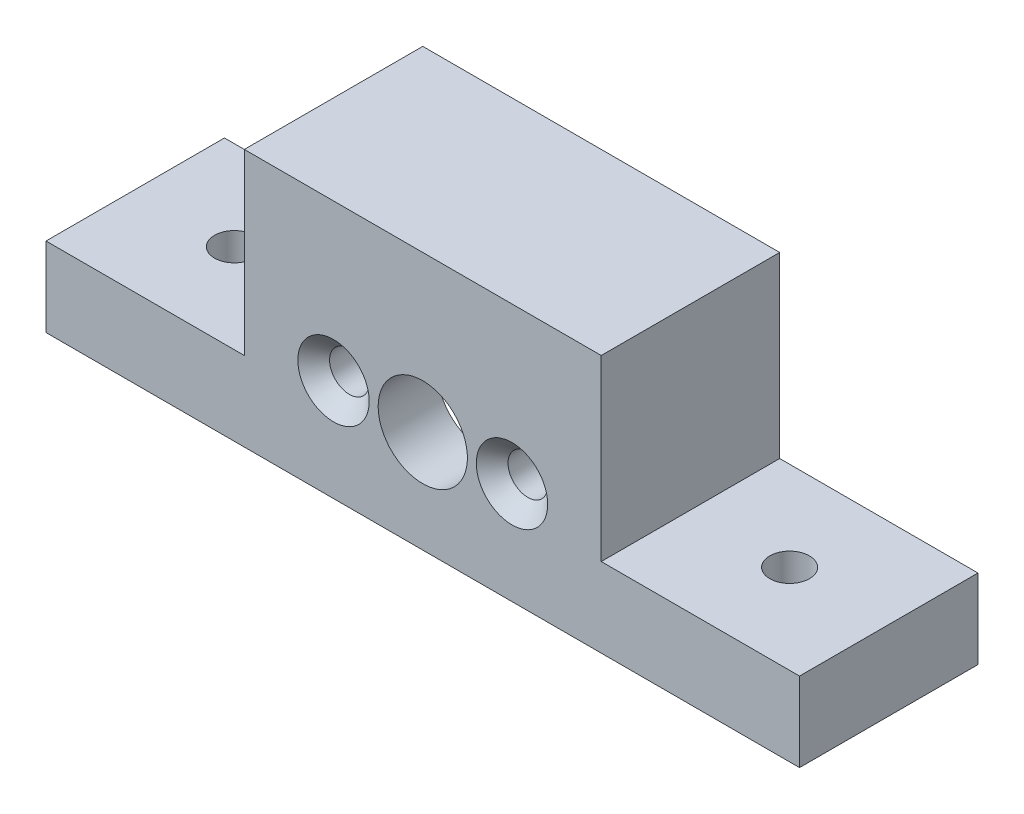
SolidWorks part; units mm, degrees
ref_plane "Front Plane" through (0, 0, 0) normal (0, 0, 1) x (1, 0, 0)
ref_plane "Top Plane" through (0, 0, 0) normal (0, 1, 0) x (1, 0, 0)
ref_plane "Right Plane" through (0, 0, 0) normal (1, 0, 0) x (0, 0, -1)
sketch "Sketch3" plane through (0, 0, 0) normal (0, 0, 1) x (1, 0, 0)
  line L1 (9, -6.5) -> (-9, -6.5)
  line L2 (9, -6.5) -> (9, 6.5)
  line L3 (9, 6.5) -> (-9, 6.5)
  line L4 (-9, -6.5) -> (-9, 6.5)
  line L5 (9, -6.5) -> (-9, 6.5) construction
  line L6 (9, 6.5) -> (-9, -6.5) construction
  point P0 (0, 0)
  dimension "D1" = 18
  dimension "D2" = 13
extrude "Boss-Extrude1" add sketch "Sketch3" along normal blind 9
sketch "Sketch9" plane through (0, 0, 0) normal (0, 0, -1) x (-1, 0, 0)
  line L0 (-9, -6.5) -> (-6.3, -6.5) construction
  line L1 (9, -6.5) -> (-9, -6.5) construction
  line L3 (-6.3, -6.5) -> (6.3, -6.5)
  line L4 (-6.3, -6.5) -> (-6.3, 3.8)
  line L5 (-6.3, 3.8) -> (6.3, 3.8)
  line L6 (6.3, -6.5) -> (6.3, 3.8)
  dimension "D1" = 2.7
  dimension "D2" = 10.3
  dimension "D3" = 12.6
extrude "Cut-Extrude2" cut sketch "Sketch9" against normal blind 6
sketch "Sketch10" plane through (0, 0, 6) normal (0, 0, -1) x (-1, 0, 0)
  line L0 (-6.3, 3.8) -> (6.3, -6.5) construction
  line L1 (-6.3, -6.5) -> (6.3, 3.8) construction
  line L2 (0, -1.35) -> (-4.5, -1.35) construction
  line L3 (0, -1.35) -> (4.5, -1.35) construction
  circle A0 centre (0, -1.35) radius 2.25
  dimension "D1" = 4.5
  dimension "D2" = 4.5
  dimension "D3" = 4.5
extrude "Cut-Extrude3" cut sketch "Sketch10" against normal through all
sketch "Sketch11" plane through (0, 0, 0) normal (0, 0, 1) x (1, 0, 0)
  line L0 (-6.3, 3.8) -> (6.3, -6.5) construction
  line L1 (-6.3, -6.5) -> (6.3, 3.8) construction
  line L2 (0, -1.35) -> (-4.5, -1.35) construction
  line L3 (0, -1.35) -> (4.5, -1.35) construction
  circle A0 centre (0, -1.35) radius 2.25
  dimension "D1" = 4.5
  dimension "D2" = 4.5
  dimension "D3" = 4.5
hole_wizard "CSK for M1.6 Countersunk Flat Head Screw2" positions "Sketch13" profile "Sketch12" countersink size "M1.6" standard "ISO" end condition through all
sketch "Sketch13" plane through (0, 0, 9) normal (0, 0, 1) x (1, 0, 0)
  point P0 (-4.5, -1.35)
  point P3 (4.5, -1.35)
sketch "Sketch12" plane through (-4.5, -1.35, 9) normal (1, 0, 0) x (0, -1, 0)
  line L0 (0, 0) -> (0, 9)
  line L1 (0, 9) -> (1, 9)
  line L2 (1, 9) -> (1, 0.8)
  line L3 (1, 0.8) -> (1.8, 0)
  line L5 (1.8, 0) -> (0, 0)
  line L6 (-1, 0.8) -> (-1.8, 0) construction
  line L11 (0, -6.35) -> (0, 107.95) construction
  dimension "Thru Hole Dia." = 2
  dimension "Thru Hole Depth" = 9
  dimension "Near C'Sink Dia." = 3.6
  dimension "Near C'Sink Angle" = 90
sketch "Sketch14" plane through (9, 0, 0) normal (1, 0, 0) x (0, 0, -1)
  line L0 (0, 0.9) -> (0, -3.6) construction
  line L1 (-9, -6.5) -> (0, -6.5)
  line L2 (-9, -6.5) -> (-9, -2.5)
  line L3 (-9, -2.5) -> (0, -2.5)
  line L4 (0, -6.5) -> (0, -2.5)
  dimension "D1" = 4
extrude "Boss-Extrude2" add sketch "Sketch14" along normal blind 10
sketch "Sketch17" plane through (0, -2.5, 0) normal (0, 1, 0) x (1, 0, 0)
  line L0 (9, -9) -> (19, 0) construction
  line L1 (9, 0) -> (19, -9) construction
  point P12 (14, -4.5)
hole_wizard "M1.6 Clearance Hole1" positions "Sketch28" profile "Sketch27" hole size "M1.6" standard "ISO" end condition through all
sketch "Sketch28" plane through (0, -2.5, 0) normal (0, 1, 0) x (1, 0, 0)
  point P0 (14, -4.5)
sketch "Sketch27" plane through (14, -2.5, 4.5) normal (1, 0, 0) x (0, 0, 1)
  line L0 (0, 0) -> (0, 4)
  line L1 (0, 4) -> (1, 4)
  line L2 (1, 4) -> (1, 0)
  line L5 (1, 0) -> (0, 0)
  line L11 (0, -6.35) -> (0, 107.95) construction
  dimension "Thru Hole Dia." = 2
  dimension "Thru Hole Depth" = 4
mirror "Mirror2" about plane through (0, 0, 0) normal (1, 0, 0) of "M1.6 Clearance Hole1", "Boss-Extrude2"
